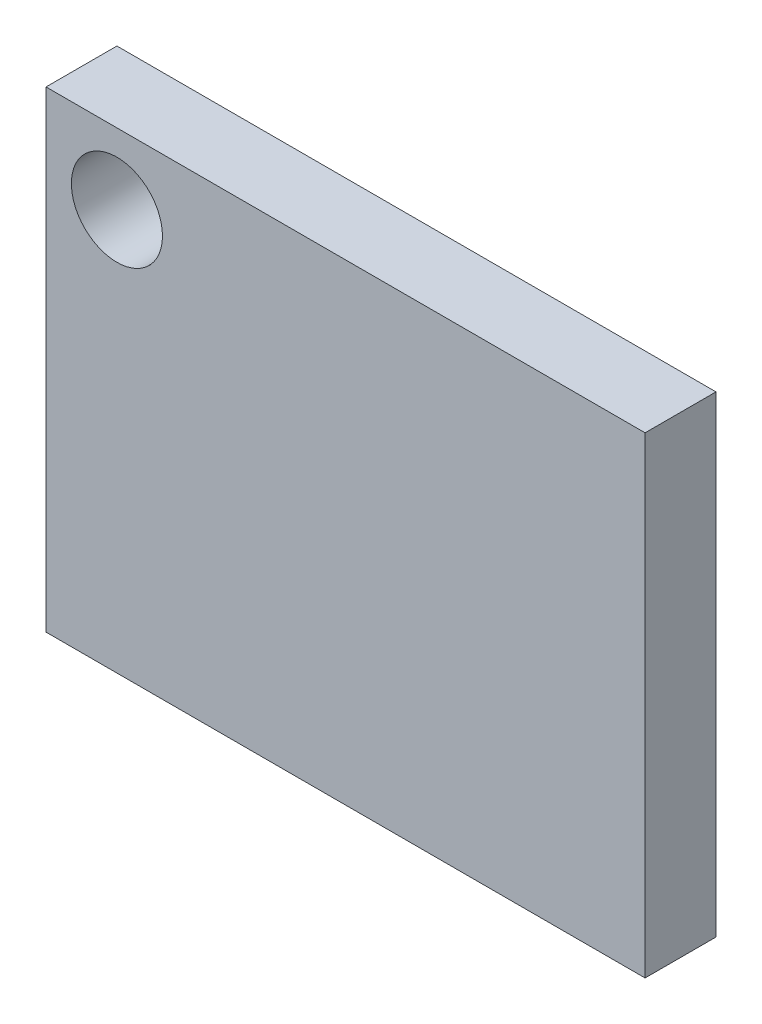
SolidWorks part; units mm, degrees
ref_plane "Front Plane" through (0, 0, 0) normal (0, 0, 1) x (1, 0, 0)
ref_plane "Top Plane" through (0, 0, 0) normal (0, 1, 0) x (1, 0, 0)
ref_plane "Right Plane" through (0, 0, 0) normal (1, 0, 0) x (0, 0, -1)
sketch "Sketch1" plane through (0, 0, 0) normal (0, 0, 1) x (1, 0, 0)
  line L1 (-10.7315, -8.4582) -> (10.7315, -8.4582)
  line L2 (-10.7315, -8.4582) -> (-10.7315, 8.4582)
  line L3 (-10.7315, 8.4582) -> (10.7315, 8.4582)
  line L4 (10.7315, -8.4582) -> (10.7315, 8.4582)
  line L5 (-10.7315, -8.4582) -> (10.7315, 8.4582) construction
  line L6 (-10.7315, 8.4582) -> (10.7315, -8.4582) construction
  point P0 (0, 0)
  dimension "D1" = 21.463
  dimension "D2" = 16.9164
extrude "Boss-Extrude1" add sketch "Sketch1" along normal blind 2.54
hole_wizard "#4 Clearance Hole1" positions "Sketch3" profile "Sketch2" hole size "#4" standard "ANSI Inch" end condition through all
sketch "Sketch3" plane through (0, 0, 2.54) normal (0, 0, 1) x (1, 0, 0)
  line L0 (10.7315, 8.4582) -> (-10.7315, 8.4582) construction
  line L1 (-10.7315, 8.4582) -> (-10.7315, -8.4582) construction
  point P0 (-8.1915, 5.9182)
  dimension "D1" = 2.54
  dimension "D2" = 2.54
sketch "Sketch2" plane through (-8.1915, 5.9182, 2.54) normal (1, 0, 0) x (0, -1, 0)
  line L0 (0, 0) -> (0, 2.54)
  line L1 (0, 2.54) -> (1.6319, 2.54)
  line L2 (1.6319, 2.54) -> (1.6319, 0)
  line L5 (1.6319, 0) -> (0, 0)
  line L11 (0, -6.35) -> (0, 107.95) construction
  dimension "Thru Hole Dia." = 3.2639
  dimension "Thru Hole Depth" = 2.54
